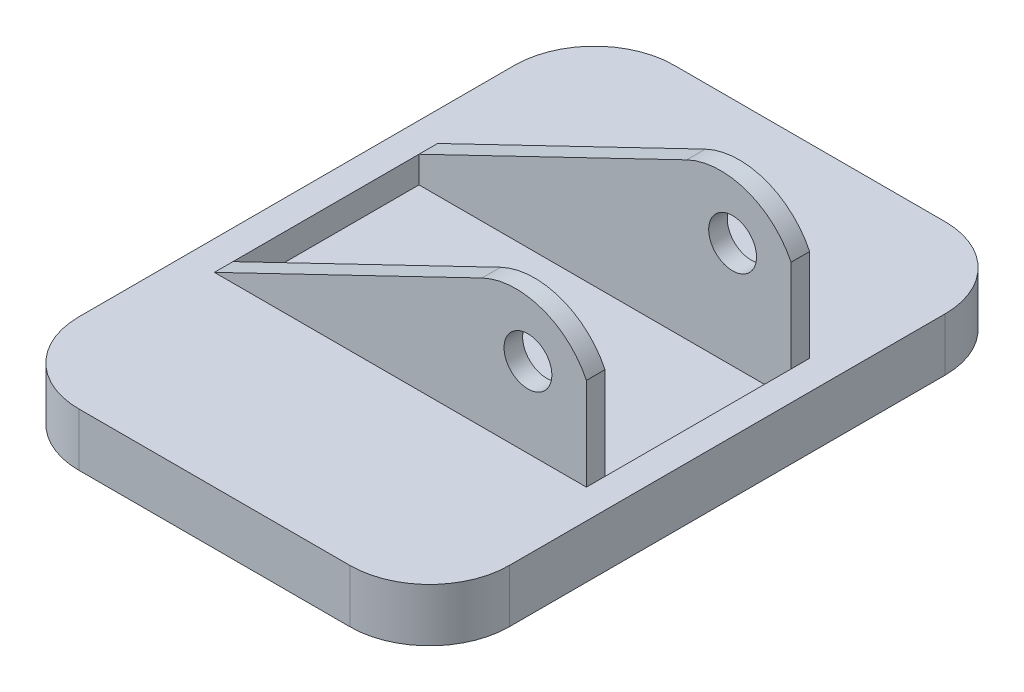
SolidWorks part; units mm, degrees
ref_plane "前视基准面" through (0, 0, 0) normal (0, 0, 1) x (1, 0, 0)
ref_plane "上视基准面" through (0, 0, 0) normal (0, 1, 0) x (1, 0, 0)
ref_plane "右视基准面" through (0, 0, 0) normal (1, 0, 0) x (0, 0, -1)
sketch "足底" plane through (0, 0, 0) normal (0, 1, 0) x (1, 0, 0)
  line L1 (15, 0) -> (66, 0)
  line L2 (0, 15) -> (0, 97)
  line L3 (15, 112) -> (66, 112)
  line L4 (81, 15) -> (81, 97)
  arc A0 (66, 0) -> (81, 15) centre (66, 15) ccw
  arc A1 (15, 0) -> (0, 15) centre (15, 15) cw
  arc A2 (81, 97) -> (66, 112) centre (66, 97) ccw
  arc A3 (0, 97) -> (15, 112) centre (15, 97) cw
  point P7 (81, 0)
  point P10 (0, 0)
  point P13 (81, 112)
  point P16 (0, 112)
  dimension "D3" = 15
  dimension "D1" = 81
  dimension "D2" = 112
extrude "凸台-拉伸1" add sketch "足底" along normal blind 10
sketch "草图2" plane through (0, 10, 0) normal (0, 1, 0) x (1, 0, 0)
  line L0 (0, 56) -> (81, 56) construction
  line L1 (0, 97) -> (0, 15) construction
  line L2 (81, 15) -> (81, 97) construction
  line L4 (5.5, 35) -> (75.5, 35)
  line L5 (5.5, 35) -> (5.5, 77)
  line L6 (5.5, 77) -> (75.5, 77)
  line L7 (75.5, 35) -> (75.5, 77)
  line L8 (5.5, 35) -> (75.5, 77) construction
  line L9 (5.5, 77) -> (75.5, 35) construction
  point P6 (40.5, 56)
  dimension "D1" = 42
  dimension "D2" = 70
extrude "凸台-拉伸2" add sketch "草图2" along normal blind 27
sketch "草图3" plane through (0, 37, 0) normal (0, 1, 0) x (1, 0, 0)
  line L0 (5.5, 56) -> (75.5, 56) construction
  line L1 (5.5, 77) -> (5.5, 35) construction
  line L2 (75.5, 35) -> (75.5, 77) construction
  line L4 (5.5, 38.5) -> (75.5, 38.5)
  line L5 (5.5, 38.5) -> (5.5, 73.5)
  line L6 (5.5, 73.5) -> (75.5, 73.5)
  line L7 (75.5, 38.5) -> (75.5, 73.5)
  line L8 (5.5, 38.5) -> (75.5, 73.5) construction
  line L9 (5.5, 73.5) -> (75.5, 38.5) construction
  point P6 (40.5, 56)
  dimension "D1" = 35
extrude "切除-拉伸1" cut sketch "草图3" against normal blind 32
sketch "草图4" plane through (0, 0, -35) normal (0, 0, 1) x (1, 0, 0)
  line L0 (40.5, 37) -> (40.5, 10) construction
  line L1 (5.5, 37) -> (75.5, 37) construction
  line L2 (5.5, 10) -> (75.5, 10) construction
  line L3 (5.5, 10) -> (2.4652, 10)
  line L4 (2.4652, 10) -> (2.4652, 42.3463)
  line L5 (2.4652, 42.3463) -> (79.0361, 42.3463)
  line L6 (79.0361, 27.3964) -> (79.0361, 42.3463)
  line L7 (75.5, 37) -> (75.5, 10) construction
  line L9 (5.5, 10) -> (55.8667, 34.2635)
  line L10 (75.5, 27.3964) -> (79.0361, 27.3964)
  circle A0 centre (64.5, 25) radius 4.5
  arc A1 (55.8667, 34.2635) -> (75.5, 27.3964) centre (62.2498, 21.0133) cw
  dimension "D1" = 9
  dimension "D2" = 15
  dimension "D3" = 24
extrude "切除-拉伸2" cut sketch "草图4" against normal through all
